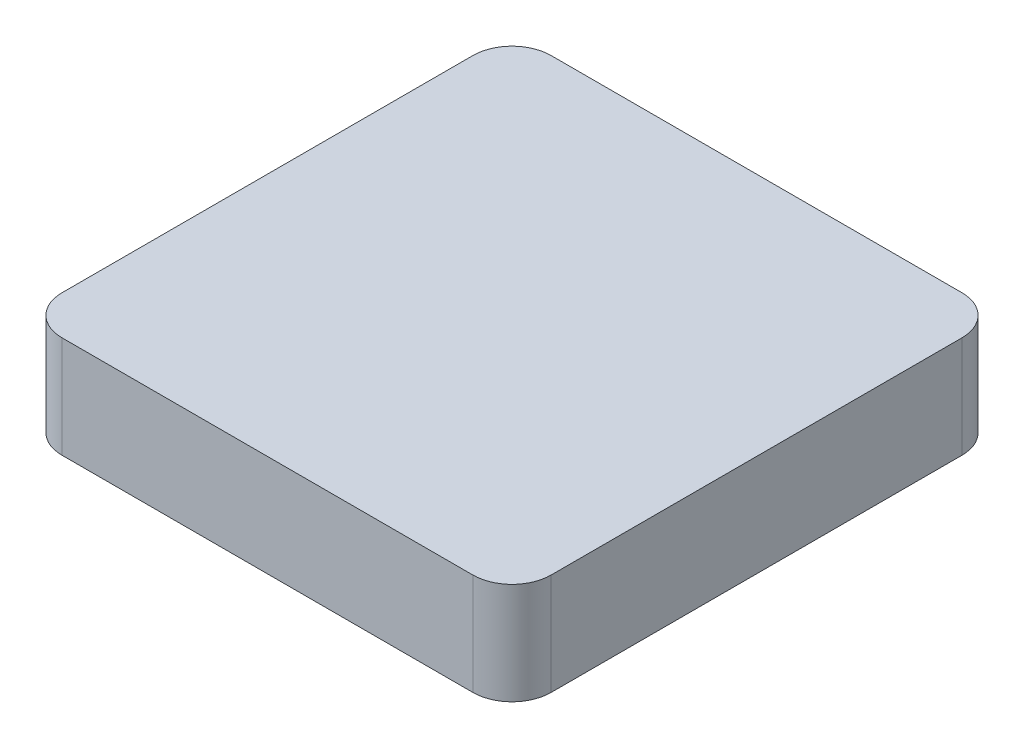
SolidWorks part; units mm, degrees
material "FR4_stuffedProtoboard"
ref_plane "Front Plane" through (0, 0, 0) normal (0, 0, 1) x (1, 0, 0)
ref_plane "Top Plane" through (0, 0, 0) normal (0, 1, 0) x (1, 0, 0)
ref_plane "Right Plane" through (0, 0, 0) normal (1, 0, 0) x (0, 0, -1)
sketch "Sketch2" plane through (0, 0, 0) normal (0, 1, 0) x (1, 0, 0)
  line L1 (-12.5, -12.5) -> (12.5, -12.5)
  line L2 (-12.5, -12.5) -> (-12.5, 12.5)
  line L3 (-12.5, 12.5) -> (12.5, 12.5)
  line L4 (12.5, -12.5) -> (12.5, 12.5)
  line L5 (-12.5, -12.5) -> (12.5, 12.5) construction
  line L6 (-12.5, 12.5) -> (12.5, -12.5) construction
  point P0 (0, 0)
  dimension "D1" = 25
  dimension "D2" = 25
extrude "Boss-Extrude1" add sketch "Sketch2" along normal blind 5.2
fillet "Fillet1" radius 2 4 edges at (-12.5, 2.6, -12.5) (12.5, 2.6, -12.5) (12.5, 2.6, 12.5) (-12.5, 2.6, 12.5)
